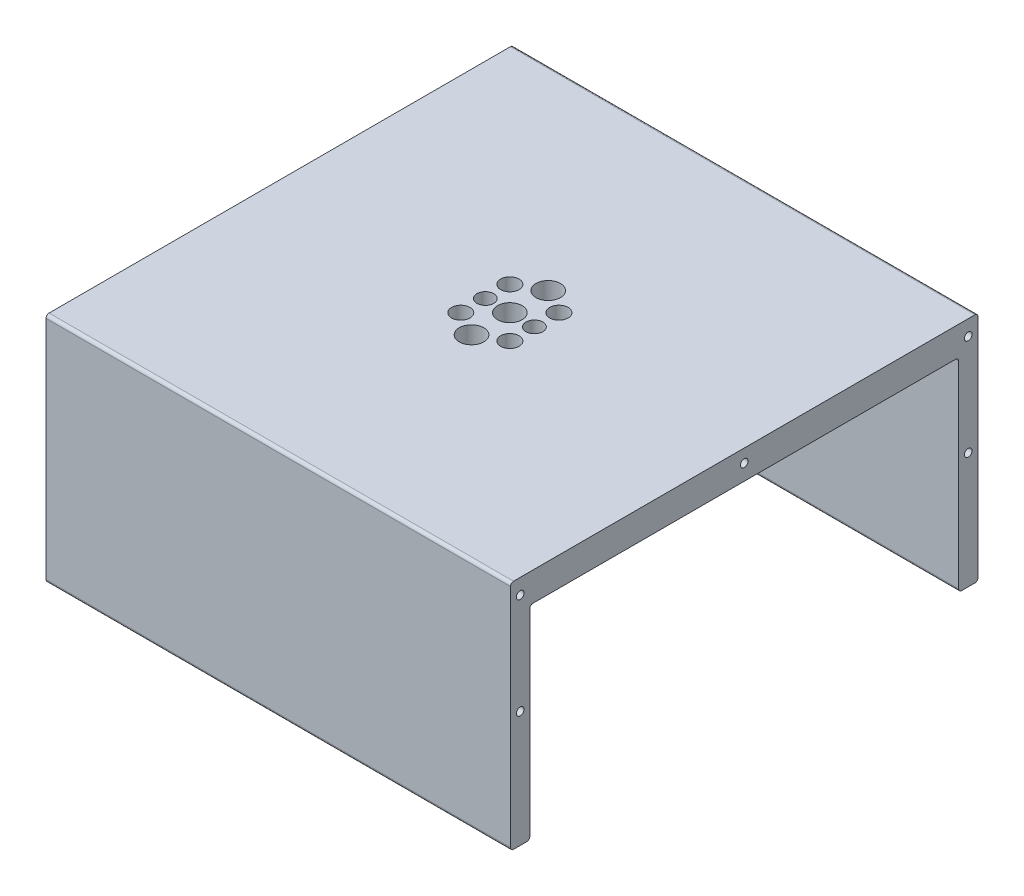
SolidWorks part; units mm, degrees
ref_plane "Front Plane" through (0, 0, 0) normal (0, 0, 1) x (1, 0, 0)
ref_plane "Top Plane" through (0, 0, 0) normal (0, 1, 0) x (1, 0, 0)
ref_plane "Right Plane" through (0, 0, 0) normal (1, 0, 0) x (0, 0, -1)
sketch "Sketch1" plane through (0, 0, 0) normal (1, 0, 0) x (0, 0, -1)
  line L0 (-69.9, -36.85) -> (-69.9, 27.45)
  line L1 (-75.2, 37.85) -> (75.2, 37.85)
  line L2 (-76.2, 36.85) -> (-76.2, -36.85)
  line L3 (-75.2, -37.85) -> (-70.9, -37.85)
  line L4 (76.2, 36.85) -> (76.2, -36.85)
  line L5 (-76.2, 37.85) -> (76.2, -37.85) construction
  line L6 (-76.2, -37.85) -> (76.2, 37.85) construction
  line L7 (-68.9, 28.45) -> (68.9, 28.45)
  line L8 (69.9, 27.45) -> (69.9, -36.85)
  line L9 (70.9, -37.85) -> (75.2, -37.85)
  arc A0 (69.9, 27.45) -> (68.9, 28.45) centre (68.9, 27.45) ccw
  arc A1 (-68.9, 28.45) -> (-69.9, 27.45) centre (-68.9, 27.45) ccw
  arc A2 (-69.9, -36.85) -> (-70.9, -37.85) centre (-70.9, -36.85) cw
  arc A3 (-75.2, -37.85) -> (-76.2, -36.85) centre (-75.2, -36.85) cw
  arc A4 (76.2, -36.85) -> (75.2, -37.85) centre (75.2, -36.85) cw
  arc A5 (70.9, -37.85) -> (69.9, -36.85) centre (70.9, -36.85) cw
  arc A6 (76.2, 36.85) -> (75.2, 37.85) centre (75.2, 36.85) ccw
  arc A7 (-75.2, 37.85) -> (-76.2, 36.85) centre (-75.2, 36.85) ccw
  point P0 (0, 0)
  point P16 (-69.9, -37.85)
  point P25 (69.9, -37.85)
  dimension "D6" = 1
  dimension "D7" = 1
  dimension "D1" = 152.4
  dimension "D2" = 75.7
  dimension "D3" = 9.4
  dimension "D4" = 6.3
  dimension "D5" = 6.3
extrude "Boss-Extrude1" add sketch "Sketch1" along normal blind 151.4
hole_wizard "Ø12.0 (12) Diameter Hole1" positions "Sketch2" profile "Sketch3" hole size "Ø12.0" standard "ISO" end condition through all
sketch "Sketch2" plane through (0, 37.85, 0) normal (0, 1, 0) x (1, 0, 0)
  point P0 (75, 0)
sketch "Sketch3" plane through (75, 37.85, 0) normal (1, 0, 0) x (0, 0, 1)
  line L0 (0, 0) -> (0, 75.7)
  line L1 (0, 75.7) -> (4, 75.7)
  line L2 (4, 75.7) -> (4, 0)
  line L5 (4, 0) -> (0, 0)
  line L11 (0, -6.35) -> (0, 107.95) construction
  dimension "Thru Hole Dia." = 8
  dimension "Thru Hole Depth" = 75.7
hole_wizard "Ø10.0 (10) Diameter Hole1" positions "Sketch4" profile "Sketch5" hole size "Ø10.0" standard "ISO" end condition through all
sketch "Sketch4" plane through (0, 37.85, 0) normal (0, 1, 0) x (1, 0, 0)
  point P17 (75, -12.5)
  point P19 (75, 0)
  point P22 (75, 12.5)
  dimension "D1" = 12.5
  dimension "D2" = 12.5
sketch "Sketch5" plane through (75, 37.85, 12.5) normal (1, 0, 0) x (0, 0, 1)
  line L0 (0, 0) -> (0, 75.7)
  line L1 (0, 75.7) -> (4, 75.7)
  line L2 (4, 75.7) -> (4, 0)
  line L5 (4, 0) -> (0, 0)
  line L11 (0, -6.35) -> (0, 107.95) construction
  dimension "Thru Hole Dia." = 8
  dimension "Thru Hole Depth" = 75.7
sketch "Sketch8" plane through (0, 0, -76.2) normal (0, 0, -1) x (-1, 0, 0)
  line L0 (-129, -7.75) -> (-122.4, -7.75)
  line L1 (-151.4, 37.85) -> (0, 37.85) construction
  line L2 (-151.4, 36.85) -> (0, 36.85) construction
  line L3 (-95.6667, -7.75) -> (-89.0667, -7.75)
  line L4 (-62.3333, -7.75) -> (-55.7333, -7.75)
  line L5 (-29, -7.75) -> (-22.4, -7.75)
  circle A0 centre (-125.7, -2.15) radius 6.5
  circle A1 centre (-92.3667, -2.15) radius 6.5
  circle A2 centre (-59.0333, -2.15) radius 6.5
  circle A3 centre (-25.7, -2.15) radius 6.5
  point P4 (-125.7, -7.75)
  point P9 (-75.7, 36.85)
  dimension "D1" = 13
  dimension "D2" = 5.6
  dimension "D3" = 40
  dimension "D4" = 50
  dimension "D5" = 4
extrude "Cut-Extrude1" [suppressed] cut sketch "Sketch8" against normal up to next contours L0 A0 | L3 A1 | L4 A2 | L5 A3
sketch "Sketch9" [suppressed] plane through (0, 0, -76.2) normal (0, 0, -1) x (-1, 0, 0)
  circle A0 centre (-125, -1.9) radius 12.5
  circle A1 centre (-91.6667, -1.9) radius 12.5
  circle A2 centre (-58.3333, -1.9) radius 12.5
  circle A3 centre (-25, -1.9) radius 12.5
  dimension "D1" = 25
  dimension "D2" = 25
  dimension "D3" = 25
  dimension "D4" = 25
extrude "Cut-Extrude2" [suppressed] cut sketch "Sketch9" against normal blind 2.8
hole_wizard "M3 Tapped Hole1" positions "Sketch13" profile "Sketch14" tap size "M3" standard "ISO"
sketch "Sketch13" plane through (151.4, 0, 0) normal (1, 0, 0) x (0, 0, -1)
  line L0 (75.2, 37.85) -> (-75.2, 37.85) construction
  line L1 (0, 33.575) -> (0, -63.382) construction
  point P0 (-73.025, 0)
  point P2 (-73.025, 32.85)
  point P4 (0, 33.575)
  point P15 (73.025, 0)
  point P16 (73.025, 32.85)
  dimension "D1" = 5
sketch "Sketch14" plane through (151.4, 0, 73.025) normal (0, 1, 0) x (0, 0, -1)
  line L0 (0, 0) -> (0, 8.2511)
  line L1 (0, 8.2511) -> (1.25, 7.5)
  line L2 (1.25, 7.5) -> (1.25, 0)
  line L5 (1.25, 0) -> (0, 0)
  line L10 (0, 8.2511) -> (-1.25, 7.5) construction
  line L11 (0, -6.35) -> (0, 107.95) construction
  dimension "Tap Drill Dia." = 2.5
  dimension "Tap Drill Depth" = 7.5
  dimension "Drill Angle" = 118
cosmetic thread "Hole Thread3" parameters "D1"=6, "D2"=3
cosmetic thread "Hole Thread4" parameters "D1"=6, "D2"=3
cosmetic thread "Hole Thread5" parameters "D1"=6, "D2"=3
cosmetic thread "Hole Thread6" parameters "D1"=6, "D2"=3
cosmetic thread "Hole Thread7" parameters "D1"=6, "D2"=3
hole_wizard "M5 Clearance Hole1" positions "Sketch17" profile "Sketch18" hole size "M5" standard "ISO" end condition through all
sketch "Sketch17" plane through (0, 37.85, 0) normal (0, 1, 0) x (1, 0, 0)
  point P0 (83, 0)
  point P3 (67, 0)
sketch "Sketch18" plane through (83, 37.85, 0) normal (1, 0, 0) x (0, 0, 1)
  line L0 (0, 0) -> (0, 75.7)
  line L1 (0, 75.7) -> (2.75, 75.7)
  line L2 (2.75, 75.7) -> (2.75, 0)
  line L5 (2.75, 0) -> (0, 0)
  line L11 (0, -6.35) -> (0, 107.95) construction
  dimension "Thru Hole Dia." = 5.5
  dimension "Thru Hole Depth" = 75.7
sketch "Sketch19" plane through (0, 37.85, 0) normal (0, 1, 0) x (1, 0, 0)
  circle A0 centre (67, 8) radius 3
  circle A1 centre (83, 8) radius 3
  circle A2 centre (83, -8) radius 3
  circle A3 centre (67, -8) radius 3
  point P2 (75, 0)
  point P13 (75, 0)
  dimension "D1" = 8
  dimension "D2" = 8
  dimension "D3" = 4
extrude "Cut-Extrude3" cut sketch "Sketch19" against normal through all
sketch "Sketch20" plane through (0, 37.85, 0) normal (0, 1, 0) x (1, 0, 0)
  circle A0 centre (74.9797, 0) radius 17.4244
